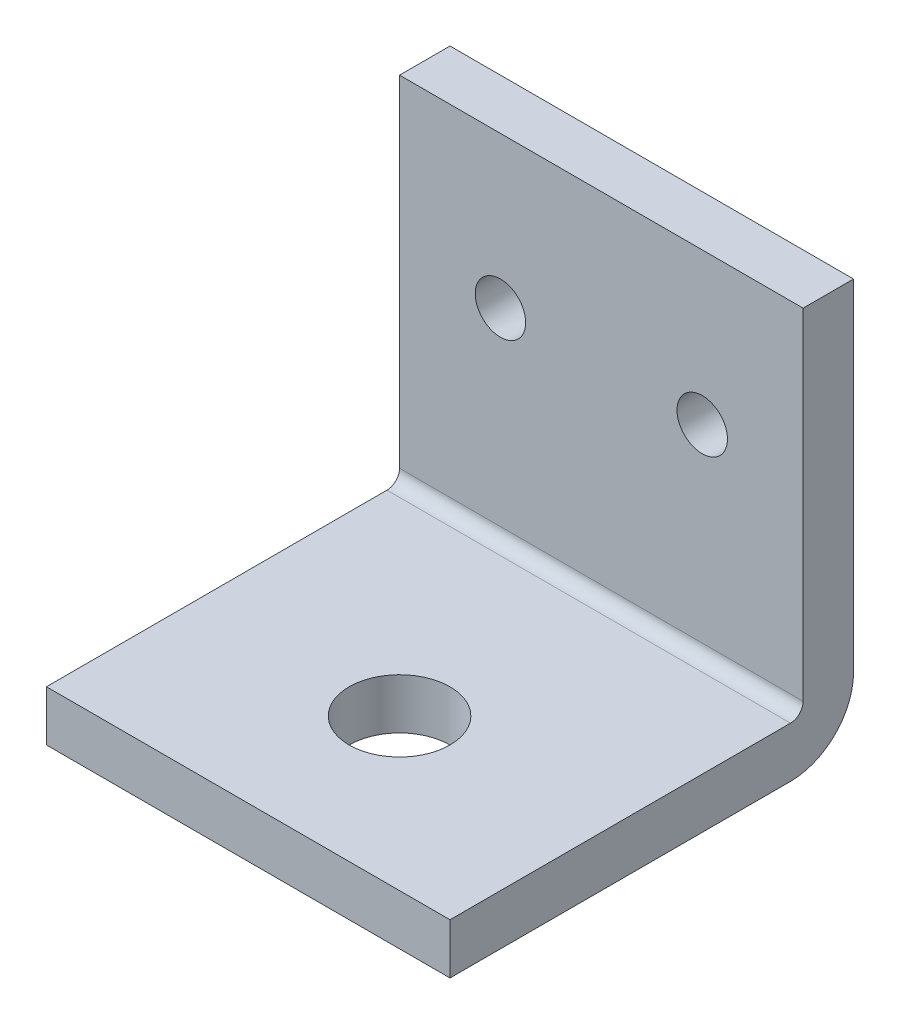
SolidWorks part; units mm, degrees
ref_plane "Front Plane" through (0, 0, 0) normal (0, 0, 1) x (1, 0, 0)
ref_plane "Top Plane" through (0, 0, 0) normal (0, 1, 0) x (1, 0, 0)
ref_plane "Right Plane" through (0, 0, 0) normal (1, 0, 0) x (0, 0, -1)
sketch "Sketch1" plane through (0, 0, 0) normal (0, 1, 0) x (1, 0, 0)
  line L1 (-20, 20) -> (20, 20)
  line L2 (-20, 20) -> (-20, -20)
  line L3 (-20, -20) -> (20, -20)
  line L4 (20, 20) -> (20, -20)
  line L5 (-20, 20) -> (20, -20) construction
  line L6 (-20, -20) -> (20, 20) construction
  point P0 (0, 0)
  dimension "D1" = 40
  dimension "D2" = 40
extrude "Boss-Extrude1" add sketch "Sketch1" along normal blind 5
sketch "Sketch2" plane through (0, 5, 0) normal (0, 1, 0) x (1, 0, 0)
  line L0 (20, -20) -> (20, 20) construction
  line L1 (-20, 20) -> (20, 20)
  line L2 (-20, 20) -> (-20, 15)
  line L3 (-20, 15) -> (20, 15)
  line L4 (20, 20) -> (20, 15)
  dimension "D1" = 5
extrude "Boss-Extrude2" add sketch "Sketch2" along normal blind 35
sketch "Sketch3" plane through (0, 5, 0) normal (0, 1, 0) x (1, 0, 0)
  line L1 (-20, -20) -> (20, -20) construction
  circle A1 centre (0, -5) radius 5
  dimension "D1" = 10
  dimension "D2" = 15
extrude "Cut-Extrude1" cut sketch "Sketch3" against normal blind 35
sketch "Sketch4" plane through (0, 0, -15) normal (0, 0, 1) x (1, 0, 0)
  line L0 (20, 40) -> (20, 5) construction
  line L1 (-20, 40) -> (-20, 5) construction
  line L2 (-20, 40) -> (20, 40) construction
  circle A0 centre (-10, 25) radius 2.5
  circle A1 centre (10, 25) radius 2.5
  dimension "D4" = 5
  dimension "D5" = 5
  dimension "D1" = 20
  dimension "D2" = 10
  dimension "D3" = 10
  dimension "D6" = 15
extrude "Cut-Extrude2" cut sketch "Sketch4" against normal blind 35
fillet "Fillet1" radius 1.25 1 edges at (0, 5, -15)
fillet "Fillet2" radius 6.25 1 edges at (0, 0, -20)
